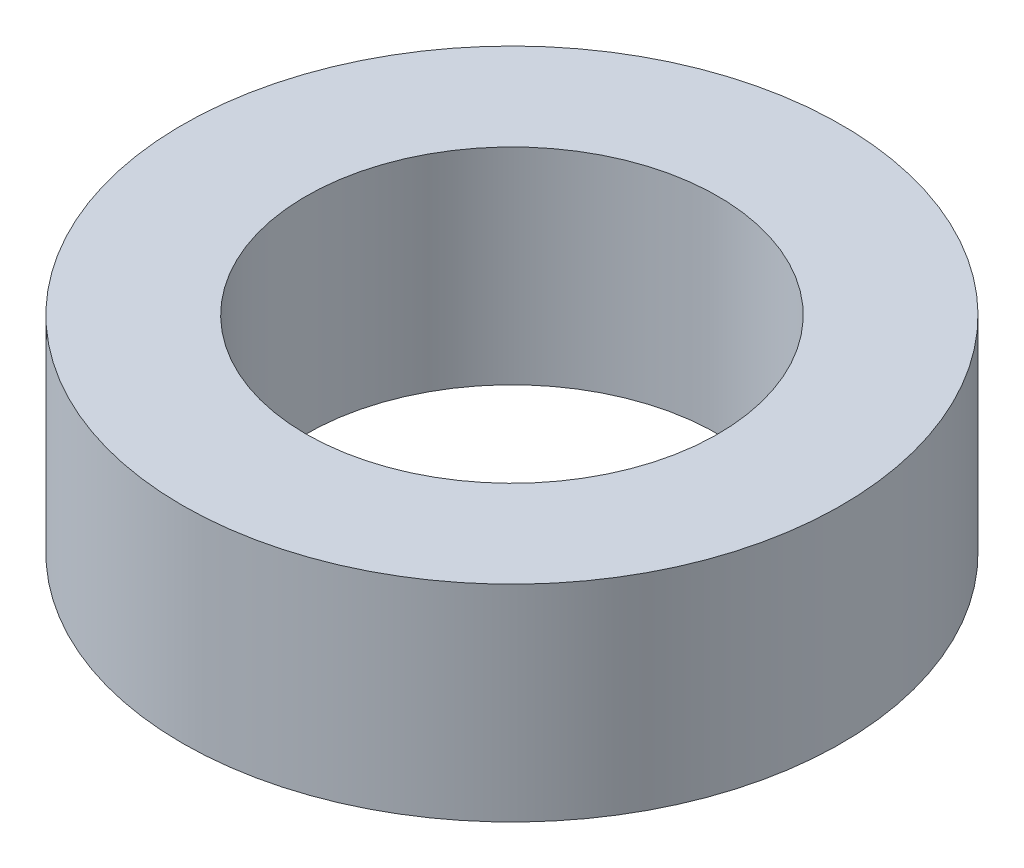
SolidWorks part; units mm, degrees
material "AISI 304"
ref_plane "Front Plane" through (0, 0, 0) normal (0, 0, 1) x (1, 0, 0)
ref_plane "Top Plane" through (0, 0, 0) normal (0, 1, 0) x (1, 0, 0)
ref_plane "Right Plane" through (0, 0, 0) normal (1, 0, 0) x (0, 0, -1)
sketch "Sketch1" plane through (0, 0, 0) normal (0, 1, 0) x (1, 0, 0)
  circle A0 centre (0, 0) radius 4
  circle A1 centre (0, 0) radius 2.5
  dimension "D1" = 8
  dimension "D2" = 5
extrude "Boss-Extrude1" add sketch "Sketch1" along normal blind 2.5
